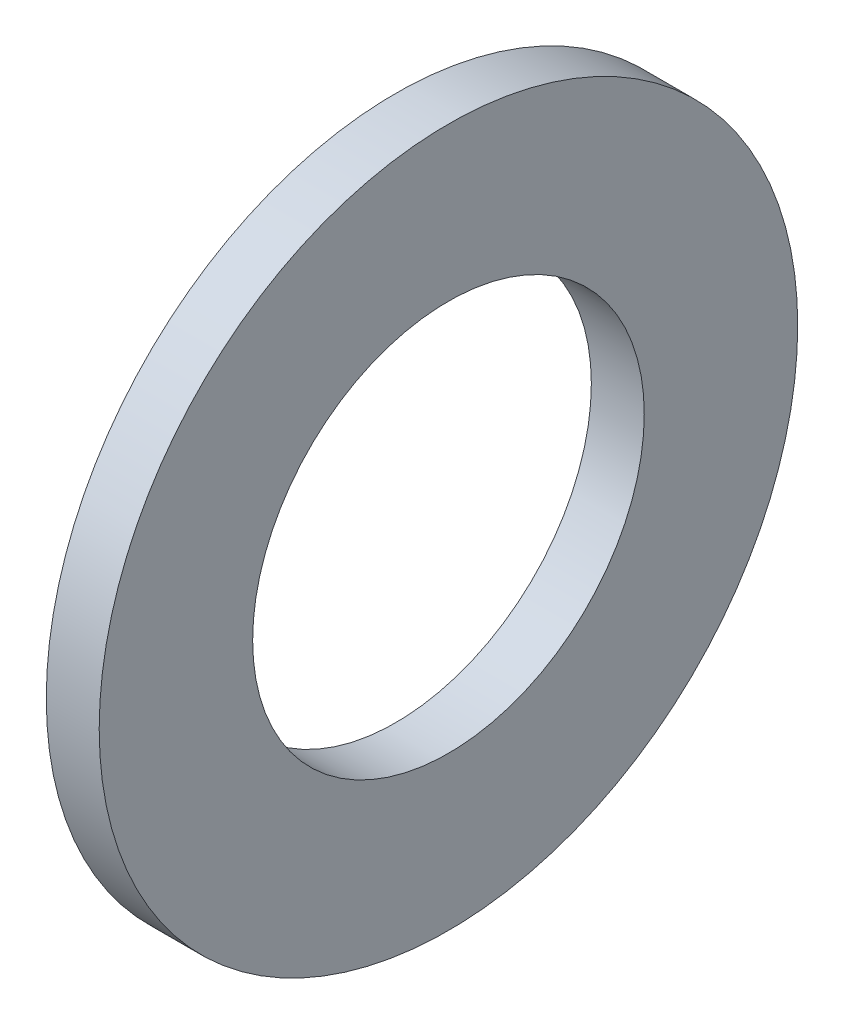
SolidWorks part; units mm, degrees
ref_plane "Plane1" through (0, 0, 0) normal (0, 0, 1) x (1, 0, 0)
ref_plane "Plane2" through (0, 0, 0) normal (0, 1, 0) x (1, 0, 0)
ref_plane "Plane3" through (0, 0, 0) normal (1, 0, 0) x (0, 0, -1)
sketch "Sketch1" plane through (0, 0, 0) normal (0, 0, 1) x (1, 0, 0)
  line L0 (-34.925, 0) -> (9.525, 0) construction
  line L1 (0, 18.5) -> (0, 33)
  line L2 (0, 33) -> (-5, 33)
  line L3 (-5, 33) -> (-5, 18.5)
  line L4 (-5, 18.5) -> (0, 18.5)
  dimension "Thickness" = 5
  dimension "Inside_dia" = 37
  dimension "Outside_dia" = 66
revolve "Base-Revolve" add sketch "Sketch1" angle 360 about L0
